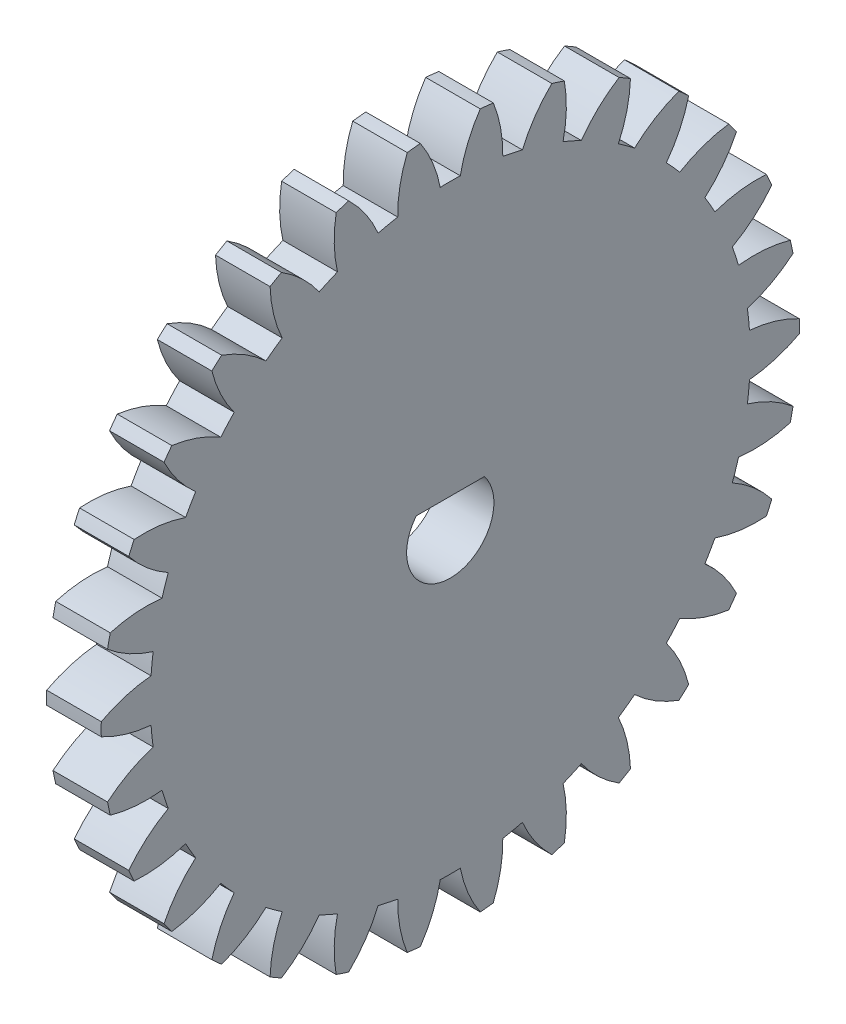
SolidWorks part; units mm, degrees
ref_plane "Plane1" through (0, 0, 0) normal (0, 0, 1) x (1, 0, 0)
ref_plane "Plane2" through (0, 0, 0) normal (0, 1, 0) x (1, 0, 0)
ref_plane "Plane3" through (0, 0, 0) normal (1, 0, 0) x (0, 0, -1)
sketch "HoldingSke" plane through (0, 0, 0) normal (0, 1, 0) x (1, 0, 0)
  line L0 (0, 0) -> (0.433, -0.25)
  line L1 (-15, 0) -> (100, 0) construction
  line L2 (0, 0) -> (-2.1039, 2.3779)
  line L3 (0, 0) -> (-11.863, 4.5341)
  line L4 (0, 0) -> (7.479, 4.318)
  line L5 (0, 0) -> (-46.8476, -17.4728)
  line L6 (0, 0) -> (-4.1448, -2.7965)
  line L7 (-2.1039, 2.3779) -> (8.6586, 51.2059)
  line L8 (-76.2, 54.61) -> (-74.8, 54.61)
  line L9 (-71.009, 38.7566) -> (-53.1078, 45.2721)
  line L10 (-76.2, 71.12) -> (104.1128, 71.12)
  line L11 (0, 0) -> (-5, 0)
  line L12 (-76.2, 101.6) -> (-76.133, 101.6)
  line L13 (24.9733, 27.94) -> (52.9518, 28.4284)
  line L14 (24.9733, 27.94) -> (24.9743, 27.94)
  line L15 (24.9733, 27.94) -> (100.4006, 29.5858)
  line L16 (-63.627, -2) -> (-12.827, -2)
  circle A0 centre (0, 0) radius 4
  circle A1 centre (0, 0) radius 27.499
  circle A2 centre (0, 0) radius 37.5
  circle A3 centre (0, 0) radius 4
  dimension "MHD" = 54.998
  dimension "Hub_dia" = 75
  dimension "Bore" = 8
  dimension "MBD" = 8
  dimension "Num_teeth" = 30
  dimension "Pitch" = 0.5
  dimension "Overall_len" = 50
  dimension "Show_teeth" = 30
  dimension "Thickness" = 5
  dimension "OAL" = 50.0001
  dimension "T_dim" = 1.4
  dimension "Ap" = 20
  dimension "H" = 19.05
  dimension "Pitch_radius" = 180.3128
  dimension "Width" = 5
  dimension "Backlash" = 0.067
  dimension "Addendum_fac" = 1
  dimension "Dedendum_fac" = 1.25
  dimension "Clearance_fac" = 0.25
  dimension "Dedendum_add" = 0.001
  dimension "Module" = 2
sketch "BasProSke" plane through (0, 0, 0) normal (0, 1, 0) x (1, 0, 0)
  line L0 (-10, 0) -> (60, 0) construction
  line L1 (0, 0) -> (0, 32)
  line L2 (0, 0) -> (5, 0)
  line L3 (5, 0) -> (5, 32)
  line L4 (5, 32) -> (0, 32)
  dimension "Thickness" = 5
  dimension "Diameter" = 64
revolve "Base-Revolve" add sketch "BasProSke" angle 360 about L0
sketch "TooCutSke" plane through (0, 0, 0) normal (1, 0, 0) x (0, 0, -1)
  line L1 (0, 0) -> (0, 107) construction
  line L2 (0, 0) -> (-1.6873, 29.9525) construction
  line L3 (0, 0) -> (-6.2643, 59.6013) construction
  line L4 (-1.6873, 29.9525) -> (-3.1322, 29.8007) construction
  arc A0 (0.9186, 27.4837) -> (-0.9186, 27.4837) centre (0, 0) ccw
  arc A1 (2.7618, 31.9061) -> (-2.7618, 31.9061) centre (0, 0) ccw
  circle A2 centre (0, 0) radius 30 construction
  circle A3 centre (0, 0) radius 28.1908 construction
  arc A4 (-0.9186, 27.4837) -> (-2.7618, 31.9061) centre (-12.6936, 25.1712) ccw
  arc A5 (2.7618, 31.9061) -> (0.9186, 27.4837) centre (12.6936, 25.1712) ccw
  dimension "Root_dia" = 54.998
  dimension "Overcut_dia" = 64.0508
  dimension "Pitch_dia" = 60
  dimension "Base_dia" = 56.3816
  dimension "Flank_rad" = 12
  dimension "Half_ang" = 6
  dimension "Half_CT" = 1.4528
extrude "ToothCut" cut sketch "TooCutSke" along normal through all
fillet "Breaks" [suppressed] radius 0.04
fillet "RootFillets" [suppressed] radius 0.501
pattern_circular "TeethCuts" count 30 every 12 about axis through (-10, 0, 0) along (1, 0, 0) of "ToothCut", "RootFillets", "Breaks"
sketch "HubNeaOneSke" plane through (0, 0, 0) normal (-1, 0, 0) x (0, 0, 1)
  circle A0 centre (0, 0) radius 27.499
  dimension "Diameter" = 54.998
extrude "HubNearOne" [suppressed] add sketch "HubNeaOneSke" along normal blind 45.0001
sketch "HubNeaBotSke" plane through (0, 0, 0) normal (-1, 0, 0) x (0, 0, 1)
  circle A0 centre (0, 0) radius 27.499
  dimension "Diameter" = 54.998
extrude "HubNearBoth" [suppressed] add sketch "HubNeaBotSke" along normal blind 22.5
ref_plane "FarPln" through (5, 0, 0) normal (1, 0, 0) x (0, 0, -1)
sketch "HubFarSke" plane through (5, 0, 0) normal (1, 0, 0) x (0, 0, -1)
  circle A0 centre (0, 0) radius 27.499
  dimension "Diameter" = 54.998
extrude "HubFar" [suppressed] add sketch "HubFarSke" along normal blind 22.5
sketch "BorSke" plane through (0, 0, 0) normal (1, 0, 0) x (0, 0, -1)
  circle A0 centre (0, 0) radius 4
  dimension "Diameter" = 8
extrude "Bore" cut sketch "BorSke" along normal mid plane 100.0001
sketch "KeySke" plane through (0, 0, 0) normal (1, 0, 0) x (0, 0, -1)
  line L0 (-1.5, 0) -> (-1.5, 5.4)
  line L1 (-1.5, 5.4) -> (1.5, 5.4)
  line L2 (1.5, 5.4) -> (1.5, 0)
  line L3 (0, 0) -> (0, 34) construction
  line L4 (-1.5, 0) -> (1.5, 0)
  dimension "Offset" = 5.4
  dimension "Width" = 3
extrude "Keyway" [suppressed] cut sketch "KeySke" along normal mid plane 100.0001
pattern_circular "Keyway2" [suppressed] count 2 every 90 about axis through (-10, 0, 0) along (1, 0, 0)
sketch "Sketch1" plane through (5, 0, 0) normal (1, 0, 0) x (0, 0, -1)
  line L0 (-3.1225, 2.5) -> (3.1225, 2.5)
  circle A0 centre (0, 0) radius 4 construction
  arc A1 (3.1225, 2.5) -> (-3.1225, 2.5) centre (0, 0) ccw
  dimension "D1" = 2.5
extrude "Boss-Extrude1" add sketch "Sketch1" against normal blind 5
equation "' \"Module@HoldingSke\" = 6.35"
equation "' \"Num_teeth@HoldingSke\" = 12"
equation "' \"Ap@HoldingSke\" =  20"
equation "' \"Ap@HoldingSke\" = 20"
equation "' \"Width@HoldingSke\" = 0.5 * 25.4"
equation "' \"Hub_dia@HoldingSke\"= 1 * 25.4"
equation "' \"Hub_dia@HoldingSke\" = 1 * 25.4"
equation "' \"Overall_len@HoldingSke\" = 1.0 * 25.4"
equation "' \"Bore@HoldingSke\" = 0.75 * 25.4"
equation "' \"T_dim@HoldingSke\" = 0.1 * 25.4"
equation "' \"Width@KeySke\" = 0.25 * 25.4"
equation "' \"Show_teeth@HoldingSke\" = 13"
equation "' \"Backlash@HoldingSke\" = 0.009 * 25.4"
equation "' \"Addendum_fac@HoldingSke\" = 1.0"
equation "' \"Dedendum_fac@HoldingSke\" = 1.25"
equation "' \"Dedendum_add@HoldingSke\" = 0.00005 * 25.4"
equation "' \"Clearance_fac@HoldingSke\" = 0.25"
equation "\"Pitch@HoldingSke\" = 1 / \"Module@HoldingSke\""
equation "\"Overcut_dia@TooCutSke\" = (\"Num_teeth@HoldingSke\" + 2 * \"Addendum_fac@HoldingSke\") / \"Pitch@HoldingSke\" + 0.002 * 25.4"
equation "\"Pitch_dia@TooCutSke\" = \"Num_teeth@HoldingSke\" / \"Pitch@HoldingSke\""
equation "\"Base_dia@TooCutSke\" = \"Num_teeth@HoldingSke\" / \"Pitch@HoldingSke\" * cos((\"Ap@HoldingSke\"  * 3.14159265 / 180))"
equation "\"Root_dia@TooCutSke\" = (\"Num_teeth@HoldingSke\" + 2) / \"Pitch@HoldingSke\" - 2 * (\"Addendum_fac@HoldingSke\" + \"Dedendum_fac@HoldingSke\") / \"Pitch@HoldingSke\" - \"Dedendum_add@HoldingSke\" * 2"
equation "\"Half_ang@TooCutSke\" = 180 / \"Num_teeth@HoldingSke\""
equation "\"Half_CT@TooCutSke\" = \"Num_teeth@HoldingSke\" / \"Pitch@HoldingSke\" * sin((3.14159265 / 2 / \"Num_teeth@HoldingSke\")) / 2 - 7 * \"Backlash@HoldingSke\" / 4"
equation "\"Flank_rad@TooCutSke\" = \"Num_teeth@HoldingSke\" / \"Pitch@HoldingSke\" / 5"
equation "\"Radius@RootFillets\" = \"Clearance_fac@HoldingSke\" / \"Pitch@HoldingSke\" + \"Dedendum_add@HoldingSke\""
equation "\"Break_rad@Breaks\" = 0.02 / \"Pitch@HoldingSke\""
equation "\"Thickness@HoldingSke\" = \"Width@HoldingSke\""
equation "\"OAL@HoldingSke\" = \"Thickness@HoldingSke\""
equation "\"MHD@HoldingSke\" = (\"Num_teeth@HoldingSke\" + 2) / \"Pitch@HoldingSke\" - 2 * (\"Addendum_fac@HoldingSke\" + \"Dedendum_fac@HoldingSke\")  / \"Pitch@HoldingSke\" - \"Dedendum_add@HoldingSke\" * 2"
equation "\"MBD@HoldingSke\" = (\"Num_teeth@HoldingSke\" + 2) / \"Pitch@HoldingSke\" - 2 * (\"Addendum_fac@HoldingSke\" + \"Dedendum_fac@HoldingSke\")  / \"Pitch@HoldingSke\" - \"Dedendum_add@HoldingSke\" * 2 - 0.002 * 25.4"
equation "\"MHD@HoldingSke\" = ((sgn( \"MHD@HoldingSke\" - \"Hub_dia@HoldingSke\" )-1)*( \"MHD@HoldingSke\" - \"Hub_dia@HoldingSke\" ))/-2+ \"Hub_dia@HoldingSke\""
equation "\"MBD@HoldingSke\" = ((sgn( \"MBD@HoldingSke\" - \"Bore@HoldingSke\" )-1)*( \"MBD@HoldingSke\" - \"Bore@HoldingSke\" ))/-2+ \"Bore@HoldingSke\""
equation "\"OAL@HoldingSke\" = ((sgn( \"OAL@HoldingSke\" - \"Overall_len@HoldingSke\" )+1)*( \"OAL@HoldingSke\" - \"Overall_len@HoldingSke\" ))/2 + \"Overall_len@HoldingSke\" + 0.000002 * 25.4"
equation "\"Num_teeth@TeethCuts\" = int( \"Show_teeth@HoldingSke\" ) + 1"
equation "\"Num_teeth@TeethCuts\" = ((sgn( \"Num_teeth@TeethCuts\" - \"Num_teeth@HoldingSke\" )-1)*( \"Num_teeth@TeethCuts\" - \"Num_teeth@HoldingSke\" ))/-2+ \"Num_teeth@HoldingSke\""
equation "\"Num_teeth@TeethCuts\" = ((sgn( \"Num_teeth@TeethCuts\" - 2.0)+1)*( \"Num_teeth@TeethCuts\" - 2.0))/2 +2.0"
equation "\"Angle@TeethCuts\" = 360.0 / \"Num_teeth@HoldingSke\""
equation "\"Diameter@BasProSke\" = (\"Num_teeth@HoldingSke\" + 2 * \"Addendum_fac@HoldingSke\") / \"Pitch@HoldingSke\""
equation "\"Thickness@BasProSke\"  = \"Thickness@HoldingSke\""
equation "' \"Fillet_rad@BasProSke\" =  \"Thickness@HoldingSke\" * 0.05"
equation "' \"Fillet_rad@BasProSke\" = \"Thickness@HoldingSke\" * 0.05"
equation "\"MHD@HoldingSke\" = ((sgn( \"MHD@HoldingSke\" - \"Root_dia@TooCutSke\" )-1)*( \"MHD@HoldingSke\" - \"Root_dia@TooCutSke\" ))/-2+ \"Root_dia@TooCutSke\""
equation "\"Diameter@HubNeaOneSke\" = \"MHD@HoldingSke\""
equation "\"Length@HubNearOne\" = \"OAL@HoldingSke\" - \"Thickness@BasProSke\""
equation "\"Diameter@HubNeaBotSke\" = \"MHD@HoldingSke\""
equation "\"Length@HubNearBoth\" = ( \"OAL@HoldingSke\" - \"Thickness@BasProSke\" ) / 2.0"
equation "\"Thickness@FarPln\" = \"Thickness@BasProSke\""
equation "\"Diameter@HubFarSke\" = \"MHD@HoldingSke\""
equation "\"Length@HubFar\" = ( \"OAL@HoldingSke\" - \"Thickness@BasProSke\" ) / 2.0"
equation "\"Diameter@BorSke\" = \"MBD@HoldingSke\""
equation "\"D1@Bore\" = \"OAL@HoldingSke\" * 2.0"
equation "\"D1@Keyway\" = \"OAL@HoldingSke\" * 2.0"
equation "\"Offset@KeySke\" = \"T_dim@HoldingSke\" + \"MBD@HoldingSke\" / 2.0"
